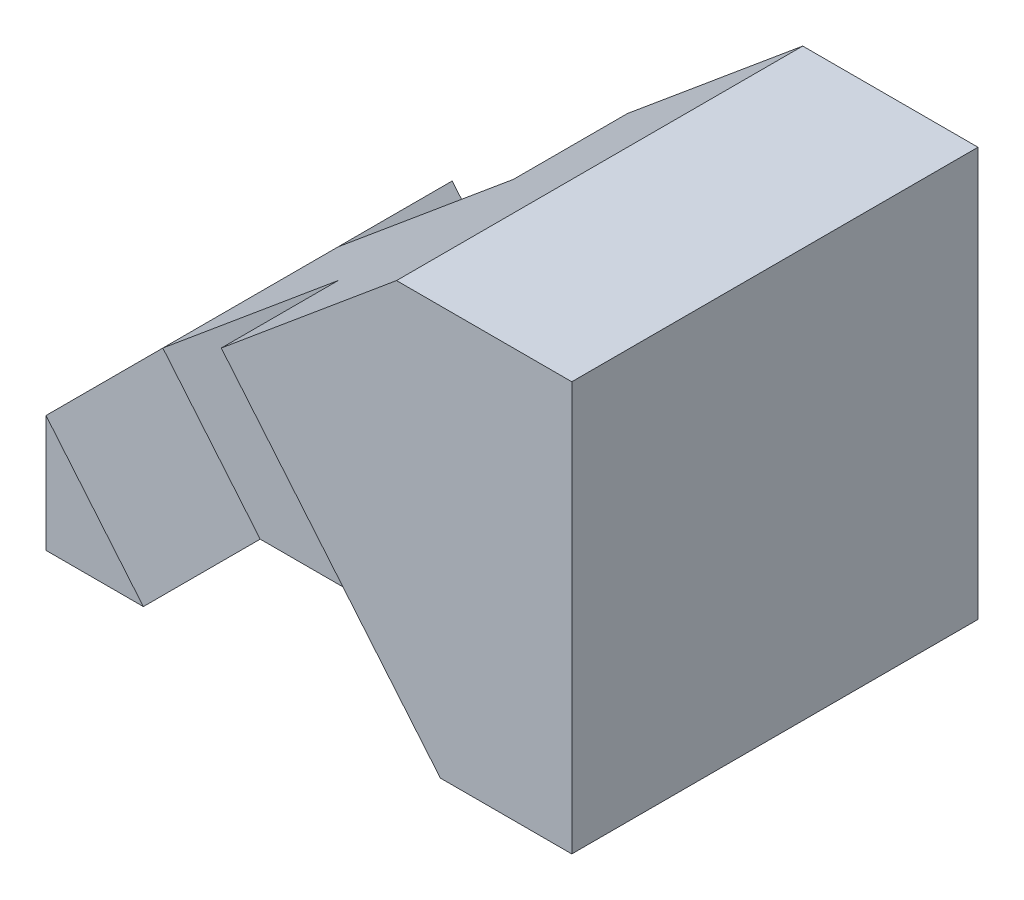
SolidWorks part; units mm, degrees
ref_plane "Front Plane" through (0, 0, 0) normal (0, 0, 1) x (1, 0, 0)
ref_plane "Top Plane" through (0, 0, 0) normal (0, 1, 0) x (1, 0, 0)
ref_plane "Right Plane" through (0, 0, 0) normal (1, 0, 0) x (0, 0, -1)
sketch "Sketch1" plane through (0, 0, 0) normal (0, 0, 1) x (1, 0, 0)
  line L0 (0, 0) -> (45000, 0)
  line L1 (45000, 0) -> (45000, 35000)
  line L2 (45000, 35000) -> (30000, 35000)
  line L3 (30000, 35000) -> (0, 10000)
  line L4 (0, 10000) -> (0, 0)
  line L5 (15000, 0) -> (15913.4645, 0)
  line L6 (15000, 0) -> (15000, 22500)
  dimension "D1" = 45000
  dimension "D2" = 35000
  dimension "D3" = 15000
  dimension "D4" = 10000
  dimension "D5" = 30000
extrude "Boss-Extrude1" add sketch "Sketch1" along normal blind 34766.003 contours L0 L6 L3 L4 | L6 L0 L1 L2 L3
sketch "Sketch2" plane through (-4918.0328, 5901.6393, 0) normal (-0.6402, 0.7682, 0) x (0.7682, 0.6402, 0)
  line L0 (45453.0924, -34766.003) -> (25927.4682, -34766.003)
  line L1 (45453.0924, -34766.003) -> (45453.0924, 0) construction
  line L2 (45453.0924, -34766.003) -> (6401.844, -34766.003) construction
  line L3 (25927.4682, -34766.003) -> (25927.4682, -24766.003)
  line L4 (25927.4682, -24766.003) -> (6401.844, -24766.003)
  line L5 (6401.844, -34766.003) -> (6401.844, 0) construction
  line L6 (6401.844, -24766.003) -> (6401.844, -9766.003)
  line L7 (6401.844, -9766.003) -> (25927.4682, -9766.003)
  line L8 (25927.4682, -9766.003) -> (25927.4682, 0)
  line L9 (45453.0924, 0) -> (6401.844, 0) construction
  line L10 (25927.4682, 0) -> (45453.0924, 0)
  line L11 (45453.0924, 0) -> (45453.0924, -34766.003)
  line M9 (45453.0924, 0) -> (6401.844, 0)
  line M10 (6401.844, 0) -> (6401.844, -34766.003)
  line M11 (6401.844, -34766.003) -> (45453.0924, -34766.003)
  dimension "D1" = 15000
  dimension "D2" = 34766.003
  dimension "D3" = 10000
  dimension "D4" = 9766.003
extrude "Cut-Extrude1" cut sketch "Sketch2" against normal blind 34999 contours L3 L4 M10 M11 | L7 L8 M9 M10
